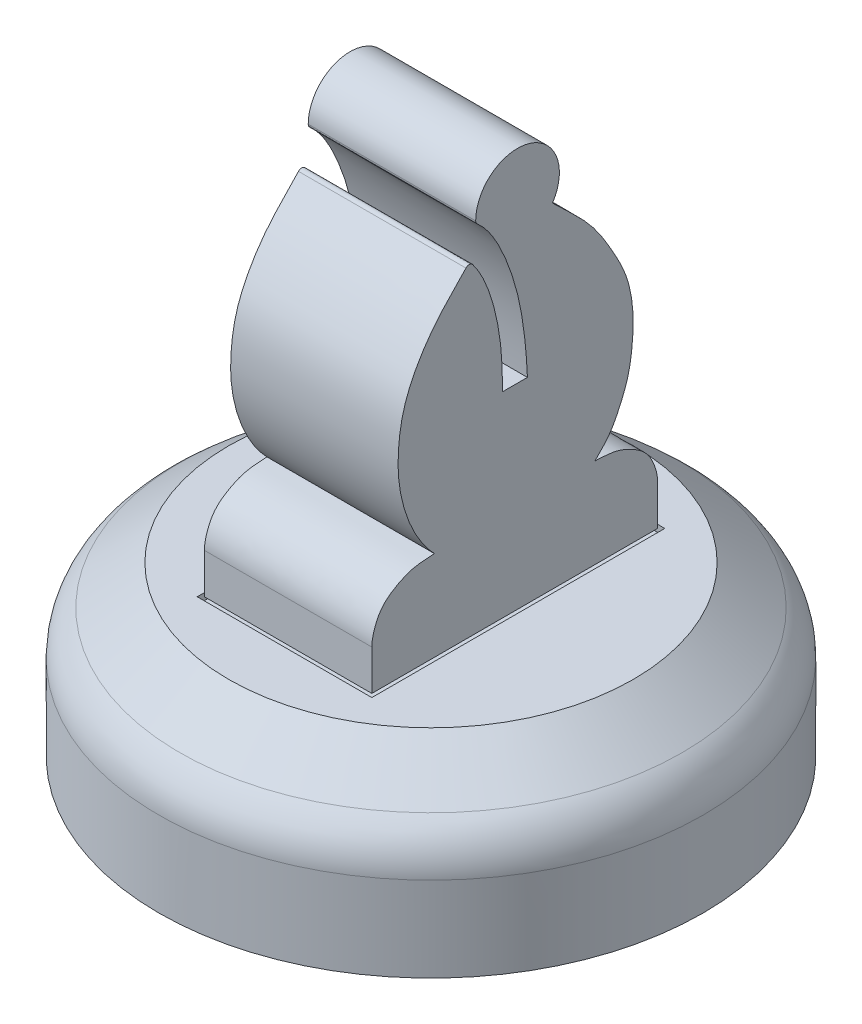
SolidWorks part; units mm, degrees
ref_plane "Front" through (0, 0, 0) normal (0, 0, 1) x (1, 0, 0)
ref_plane "Top" through (0, 0, 0) normal (0, 1, 0) x (1, 0, 0)
ref_plane "Right" through (0, 0, 0) normal (1, 0, 0) x (0, 0, -1)
sketch "Sketch1" plane through (0, 0, 0) normal (0, 1, 0) x (1, 0, 0)
  circle A0 centre (0, 0) radius 15.4781
  dimension "D1" = 30.9562
extrude "Boss-Extrude1" add sketch "Sketch1" along normal blind 6.35
sketch "Sketch2" plane through (0, 0, 0) normal (0, 0, 1) x (1, 0, 0)
  line L0 (-15.4781, 6.35) -> (-11.5094, 9.525)
  line L1 (-11.5094, 9.525) -> (0, 9.525)
  line L2 (0, 9.525) -> (0, 6.35)
  line L3 (15.4781, 6.35) -> (-15.4781, 6.35) construction
  line L4 (0, 6.35) -> (-15.4781, 6.35)
  line L5 (-15.4781, 0) -> (15.4781, 0) construction
  dimension "D1" = 3.9688
  dimension "D2" = 9.525
revolve "Revolve1" add sketch "Sketch2" angle 360 about L2
fillet "Fillet1" radius 3.175 1 edges at (0, 6.35, 15.4781)
sketch "Sketch3" plane through (0, 0, 0) normal (0, -1, 0) x (1, 0, 0)
  line L1 (-6.4516, -9.6266) -> (6.4516, -9.6266)
  line L2 (-6.4516, -9.6266) -> (-6.4516, 9.6266)
  line L3 (-6.4516, 9.6266) -> (6.4516, 9.6266)
  line L4 (6.4516, -9.6266) -> (6.4516, 9.6266)
  line L5 (-6.4516, -9.6266) -> (6.4516, 9.6266) construction
  line L6 (-6.4516, 9.6266) -> (6.4516, -9.6266) construction
  point P0 (0, 0)
  dimension "D1" = 19.2532
  dimension "D2" = 12.9032
extrude "Cut-Extrude1" cut sketch "Sketch3" against normal blind 4.7625
hole_wizard "#6 (0.204) Diameter Hole1" positions "Sketch4" profile "Sketch5" hole size "#6" standard "ANSI Inch" end condition through all
sketch "Sketch4" plane through (0, 4.7625, 0) normal (0, -1, 0) x (-1, 0, 0)
  point P0 (0, 0)
sketch "Sketch5" plane through (0, 4.7625, 0) normal (1, 0, 0) x (0, 0, -1)
  line L0 (0, 0) -> (0, 4.7625)
  line L1 (0, 4.7625) -> (2.5908, 4.7625)
  line L2 (2.5908, 4.7625) -> (2.5908, 0)
  line L5 (2.5908, 0) -> (0, 0)
  line L11 (0, -6.35) -> (0, 107.95) construction
  dimension "Thru Hole Dia." = 5.1816
  dimension "Thru Hole Depth" = 4.7625
sketch "Sketch6" plane through (0, 0, 0) normal (1, 0, 0) x (0, 0, -1)
  line L0 (154.5719, 369.3013) -> (325.2386, 369.3013) construction
  line L1 (11.5094, 9.525) -> (-11.5094, 9.525) construction
  line L2 (8.128, 9.525) -> (-8.128, 9.525)
  line L3 (8.128, 9.525) -> (8.128, 11.811)
  line L4 (-8.128, 9.525) -> (-8.128, 11.811)
  line L5 (0, 50) -> (0, -50) construction
  line L6 (1.8791, 29.8523) -> (-1.539, 29.8523) construction
  line L7 (0.1595, 31.5969) -> (0.1595, 29.8523) construction
  line L8 (0.7215, 20.6684) -> (-0.7028, 20.6684)
  arc A0 (2.1473, 28.5425) -> (-2.2178, 29.7302) centre (0.1595, 29.8523) ccw
  spline S0 degree 3 poles (8.128, 11.811) (8.128, 11.9649) (8.0881, 12.2878) (7.921, 12.8218) (7.6605, 13.3674) (7.2373, 13.7996) (6.7872, 14.0934) (6.3592, 14.3174) (5.6312, 14.592) (5.0186, 14.6061) (4.5675, 14.6331) knots 0 0 0 0 0.091822 0.189226 0.3311 0.444001 0.54183 0.647961 0.729131 1 1 1 1
  spline S1 degree 3 poles (-8.128, 11.811) (-8.128, 11.9649) (-8.0881, 12.2878) (-7.921, 12.8218) (-7.6605, 13.3674) (-7.2373, 13.7996) (-6.7872, 14.0934) (-6.3592, 14.3174) (-5.6312, 14.592) (-5.0186, 14.6061) (-4.5675, 14.6331) knots 0 0 0 0 0.091822 0.189226 0.3311 0.444001 0.54183 0.647961 0.729131 1 1 1 1
  spline S2 degree 3 poles (4.5675, 14.6331) (4.8653, 14.935) (5.4091, 15.4744) (5.9693, 16.5736) (6.4574, 17.729) (6.7446, 19.4447) (6.7856, 21.1984) (6.3381, 23.051) (5.6688, 24.2933) (4.9656, 25.5054) (4.3015, 26.4194) (3.3053, 27.4533) (2.5985, 28.0975) (2.1473, 28.5425) knots 0 0 0 0 0.080159 0.141654 0.230515 0.314789 0.467006 0.556742 0.669627 0.730469 0.820324 0.880913 1 1 1 1
  spline S3 degree 3 poles (-2.2178, 29.7302) (-1.6215, 29.2384) (-0.9954, 28.2444) (-0.3271, 26.7034) (0.44, 24.3371) (0.6505, 22.2279) (0.7215, 20.6684) knots 0 0 0 0 0.236294 0.354063 0.517817 1 1 1 1
  spline S4 degree 3 poles (-0.7028, 20.6684) (-0.6745, 21.895) (-0.8024, 23.7053) (-1.4706, 26.1981) (-2.0646, 27.4202) (-2.5771, 28.0112) knots 0 0 0 0 0.477136 0.699697 1 1 1 1
  spline S5 degree 3 poles (-2.5771, 28.0112) (-3.2491, 27.3023) (-4.4686, 26.1279) (-5.6484, 24.317) (-6.3317, 22.7376) (-6.6343, 21.1021) (-6.6727, 19.0261) (-6.0635, 16.7048) (-5.1516, 15.2381) (-4.5675, 14.6331) knots 0 0 0 0 0.193953 0.333678 0.425379 0.533262 0.661024 0.834598 1 1 1 1
  point P6 (0, 9.525)
  dimension "D1" = 16.256
  dimension "D2" = 2.286
extrude "Boss-Extrude2" add sketch "Sketch6" along normal mid plane 9.525 separate body
sketch "Sketch7" plane through (0, 9.525, 0) normal (0, 1, 0) x (1, 0, 0)
  line L14 (-4.9657, -8.3312) -> (4.9657, -8.3312)
  line L15 (-4.9657, 8.3312) -> (-4.9657, -8.3312)
  line L16 (4.9657, -8.3312) -> (4.9657, 8.3312)
  line L17 (4.9657, 8.3312) -> (-4.9657, 8.3312)
  line L18 (-4.9657, -8.3312) -> (4.9657, -8.3312)
  line L19 (-4.9657, 8.3312) -> (-4.9657, -8.3312)
  line L20 (4.9657, -8.3312) -> (4.9657, 8.3312)
  line L21 (4.9657, 8.3312) -> (-4.9657, 8.3312)
  dimension "D1" = 0.2032
extrude "Cut-Extrude2" cut sketch "Sketch7" against normal blind 0.3969
fillet "Fillet2" radius 0.254 2 edges at (0, 28.0112, 2.5771) (0, 29.7302, 2.2178)
